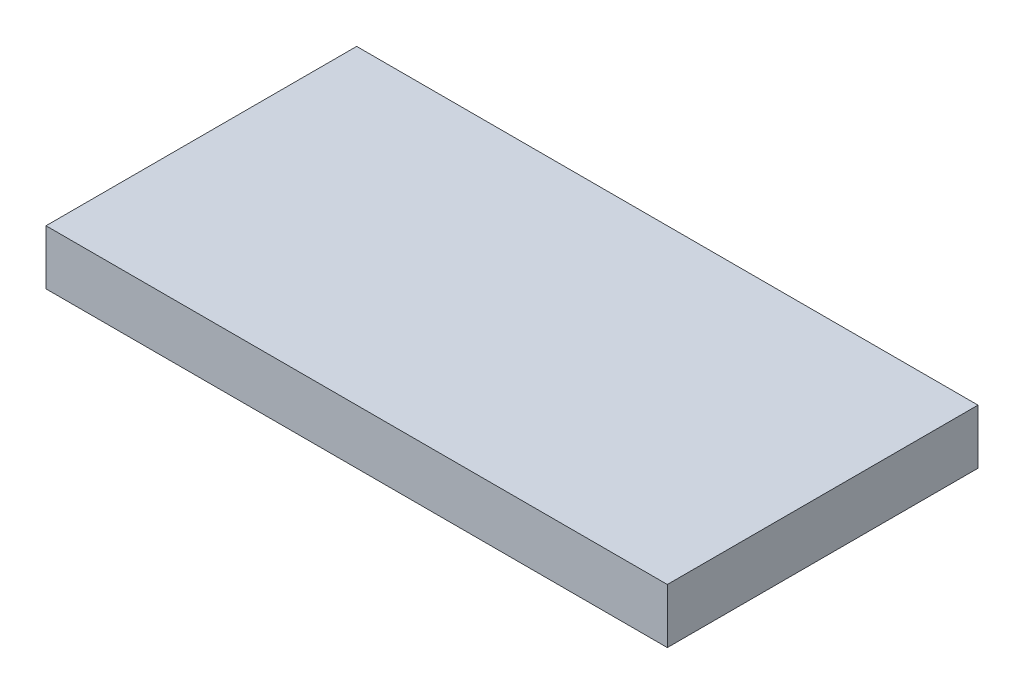
SolidWorks part; units mm, degrees
ref_plane "Front" through (0, 0, 0) normal (0, 0, 1) x (1, 0, 0)
ref_plane "Top" through (0, 0, 0) normal (0, 1, 0) x (1, 0, 0)
ref_plane "Right" through (0, 0, 0) normal (1, 0, 0) x (0, 0, -1)
sketch "Эскиз1" plane through (0, 0, 0) normal (0, 1, 0) x (1, 0, 0)
  line L1 (0, 0) -> (25, 0)
  line L2 (0, 0) -> (0, -12.5)
  line L3 (0, -12.5) -> (25, -12.5)
  line L4 (25, 0) -> (25, -12.5)
  dimension "D1" = 25
  dimension "D2" = 12.5
extrude "Бобышка-Вытянуть1" add sketch "Эскиз1" along normal blind 2.2
